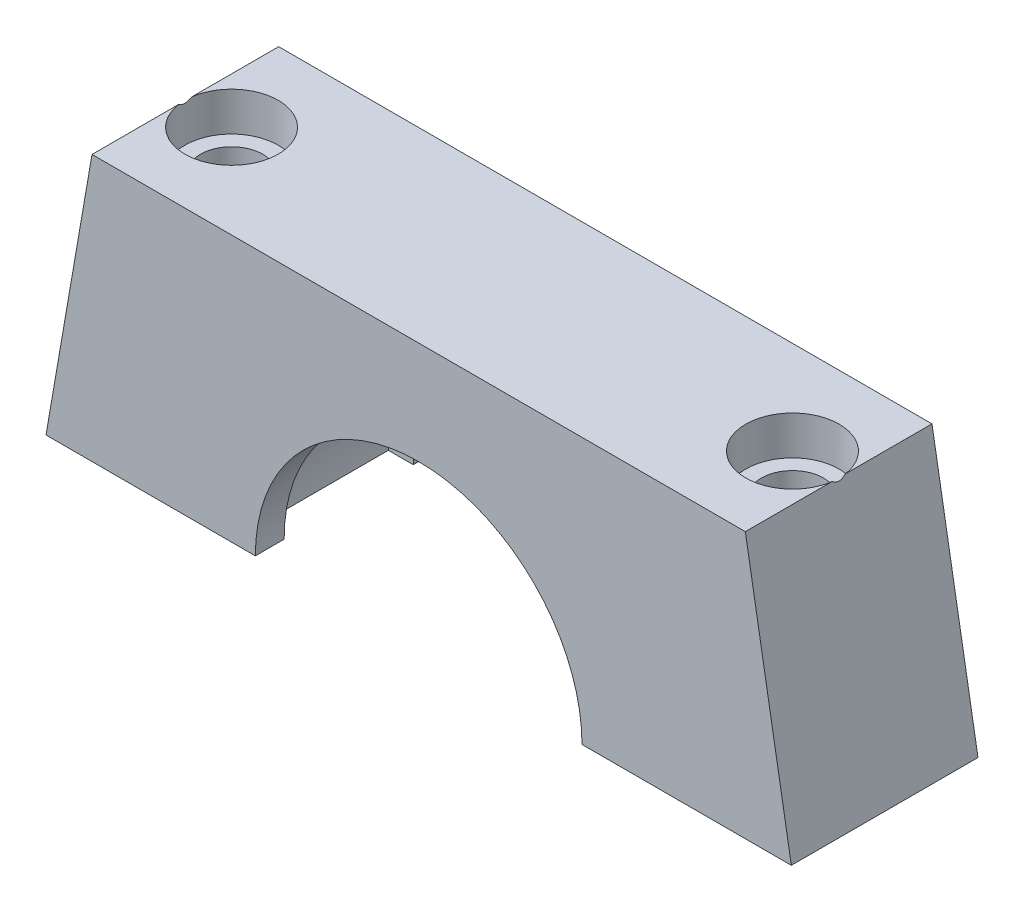
SolidWorks part; units mm, degrees
material "PET"
ref_plane "Piano frontale" through (0, 0, 0) normal (0, 0, 1) x (1, 0, 0)
ref_plane "Piano superiore" through (0, 0, 0) normal (0, 1, 0) x (1, 0, 0)
ref_plane "Piano destro" through (0, 0, 0) normal (1, 0, 0) x (0, 0, -1)
sketch "Schizzo1" plane through (0, 0, 0) normal (0, 0, 1) x (1, 0, 0)
  line L0 (-42, -54.5) -> (42, -54.5)
  line L1 (21, -17.1) -> (-21, -17.1)
  line L2 (21, -17.1) -> (21, 17.1)
  line L3 (21, 17.1) -> (-21, 17.1)
  line L4 (-21, -17.1) -> (-21, 17.1)
  line L5 (21, -17.1) -> (-21, 17.1) construction
  line L6 (21, 17.1) -> (-21, -17.1) construction
  line L7 (-42, -54.5) -> (-42, -46.5)
  line L8 (-42, -46.5) -> (-32, -46.5)
  line L9 (-32, -46.5) -> (-21, 17.1)
  line L10 (21, 17.1) -> (32, -46.5)
  line L11 (32, -46.5) -> (42, -46.5)
  line L12 (42, -46.5) -> (42, -54.5)
  line L13 (-23.9575, 0) -> (23.9575, 0)
  circle A0 centre (0, 0) radius 12.1
  point P9 (0, -54.5)
  point P16 (0, 0)
  dimension "D2" = 24.2
  dimension "D1" = 54.5
  dimension "D3" = 42
  dimension "D4" = 84
  dimension "D5" = 17.1
  dimension "D6" = 10
  dimension "D7" = 8
extrude "Estrusione-Estrusione1" add sketch "Schizzo1" along normal blind 12 contours A0 L13 L2 L3 L4 | L9 L13 L4 | L2 L13 L10
sketch "Schizzo2" plane through (0, 0, 0) normal (0, -1, 0) x (1, 0, 0)
  line L0 (-23.9575, 6) -> (-12.1, 6) construction
  line L1 (-23.9575, 12) -> (-23.9575, 0) construction
  line L2 (-12.1, 12) -> (-12.1, 0) construction
  line L3 (12.1, 6) -> (23.9575, 6) construction
  line L4 (12.1, 12) -> (12.1, 0) construction
  line L5 (23.9575, 12) -> (23.9575, 0) construction
  circle A0 centre (-18.0288, 6) radius 2
  circle A1 centre (18.0288, 6) radius 2
  dimension "D1" = 4
extrude "Taglio-Estrusione1" cut sketch "Schizzo2" against normal through all
sketch "Schizzo3" plane through (0, 17.1, 0) normal (0, 1, 0) x (1, 0, 0)
  circle A0 centre (-18.0288, -6) radius 3
  circle A1 centre (18.0288, -6) radius 3
  dimension "D1" = 6
extrude "Taglio-Estrusione2" cut sketch "Schizzo3" against normal blind 2.5
sketch "Schizzo4" plane through (0, 0, 12) normal (0, 0, 1) x (1, 0, 0)
  line L0 (-12.1, 0) -> (12.1, 0)
  circle A0 centre (0, 0) radius 10.5
  arc A1 (12.1, 0) -> (-12.1, 0) centre (0, 0) ccw construction
  arc A2 (12.1, 0) -> (-12.1, 0) centre (0, 0) ccw
  arc M2 (-12.1, 0) -> (12.1, 0) centre (0, 0) cw
  dimension "D1" = 21
extrude "Estrusione-Estrusione2" add sketch "Schizzo4" against normal blind 1.85 contours A0 L0 M2
sketch "Schizzo5" plane through (0, 0, 0) normal (0, 0, -1) x (-1, 0, 0)
  line L2 (10.5, 0) -> (12.1, 0)
  line L3 (-12.1, 0) -> (-10.5, 0)
  line L4 (10.5, 0) -> (12.1, 0)
  line L5 (-12.1, 0) -> (-10.5, 0)
  arc A2 (10.5, 0) -> (-10.5, 0) centre (0, 0) ccw
  arc A3 (12.1, 0) -> (-12.1, 0) centre (0, 0) ccw
  arc A4 (10.5, 0) -> (-10.5, 0) centre (0, 0) ccw
  arc A5 (12.1, 0) -> (-12.1, 0) centre (0, 0) ccw
  dimension "D1" = 0
extrude "Estrusione-Estrusione3" add sketch "Schizzo5" against normal blind 1.85
